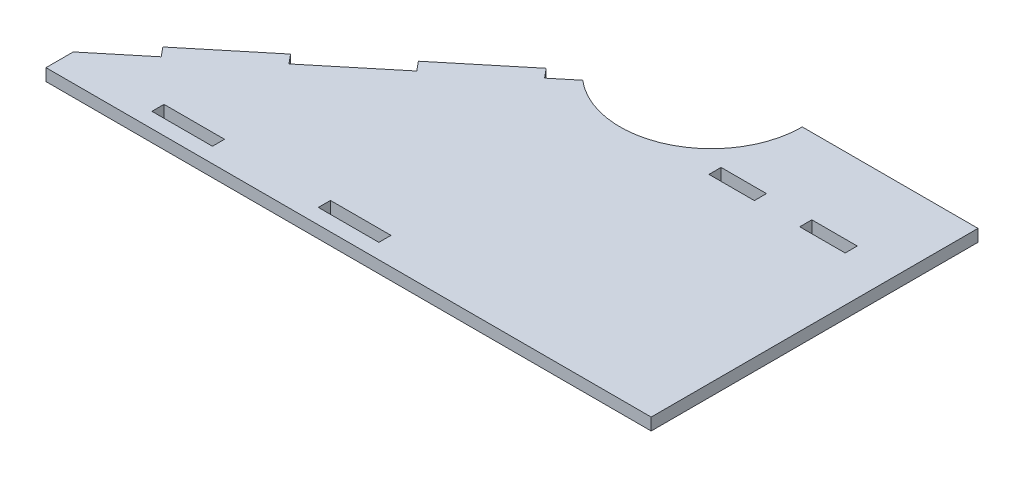
SolidWorks part; units mm, degrees
ref_plane "Front Plane" through (0, 0, 0) normal (0, 0, 1) x (1, 0, 0)
ref_plane "Top Plane" through (0, 0, 0) normal (0, 1, 0) x (1, 0, 0)
ref_plane "Right Plane" through (0, 0, 0) normal (1, 0, 0) x (0, 0, -1)
sketch "Sketch1" plane through (0, 0, 0) normal (0, 1, 0) x (1, 0, 0)
  line L1 (0, 0) -> (200, 0)
  line L2 (0, 0) -> (0, 108)
  line L3 (0, 108) -> (200, 108)
  line L4 (200, 0) -> (200, 108)
  dimension "D1" = 200
  dimension "D2" = 108
extrude "Boss-Extrude1" add sketch "Sketch1" along normal blind 4
sketch "Sketch3" plane through (0, 4, 0) normal (0, 1, 0) x (1, 0, 0)
  line L0 (120.0993, 108) -> (0, 9)
  line L1 (200, 108) -> (0, 108) construction
  line L2 (0, 108) -> (0, 0) construction
  line L3 (125, 9) -> (105, 9) construction
  line L4 (0, 9) -> (0, 108)
  line L5 (0, 108) -> (120.0993, 108)
extrude "Cut-Extrude1" cut sketch "Sketch3" against normal through all
sketch "Sketch4" plane through (-4.4173, 0, -5.3587) normal (-0.6361, 0, -0.7716) x (-0.7716, 0, 0.6361)
  line L0 (-5.7246, 4) -> (-161.3679, 4) construction
  line L1 (-116.3679, 4) -> (-86.3679, 4)
  line L2 (-116.3679, 4) -> (-116.3679, 0)
  line L3 (-116.3679, 0) -> (-86.3679, 0)
  line L4 (-86.3679, 4) -> (-86.3679, 0)
  line L5 (-5.7246, 0) -> (-161.3679, 0) construction
  line L6 (-56.3679, 4) -> (-26.3679, 4)
  line L7 (-56.3679, 4) -> (-56.3679, 0)
  line L8 (-56.3679, 0) -> (-26.3679, 0)
  line L9 (-26.3679, 4) -> (-26.3679, 0)
  line L10 (-161.3679, 0) -> (-161.3679, 4) construction
  dimension "D1" = 30
  dimension "D3" = 45
  dimension "D2" = 2
extrude "Boss-Extrude2" add sketch "Sketch4" along normal blind 4
sketch "Sketch5" plane through (0, 4, 0) normal (0, 1, 0) x (1, 0, 0)
  line L1 (185.0941, 82.9999) -> (170.0941, 82.9999)
  line L2 (185.0941, 82.9999) -> (185.0941, 78.9999)
  line L3 (185.0941, 78.9999) -> (170.0941, 78.9999)
  line L4 (170.0941, 82.9999) -> (170.0941, 78.9999)
  line L5 (155.0941, 82.9999) -> (140.0941, 82.9999)
  line L6 (155.0941, 82.9999) -> (155.0941, 78.9999)
  line L7 (155.0941, 78.9999) -> (140.0941, 78.9999)
  line L8 (140.0941, 82.9999) -> (140.0941, 78.9999)
  line L9 (105, 9) -> (85, 9)
  line L10 (105, 9) -> (105, 5)
  line L11 (105, 5) -> (85, 5)
  line L12 (85, 9) -> (85, 5)
  line L13 (50, 9) -> (30, 9)
  line L14 (50, 9) -> (50, 5)
  line L15 (50, 5) -> (30, 5)
  line L16 (30, 9) -> (30, 5)
extrude "Cut-Extrude2" cut sketch "Sketch5" against normal through all
sketch "Sketch6" plane through (0, 4, 0) normal (0, 1, 0) x (1, 0, 0)
  line L0 (200, 108) -> (120.0993, 108) construction
  circle A0 centre (111.8195, 108) radius 30.1188
  point P2 (115.3056, 107.1221)
  point P3 (120.0993, 108)
  point P6 (0, 0)
  point P7 (111.8195, 108)
extrude "Cut-Extrude4" cut sketch "Sketch6" against normal through all contours A0
